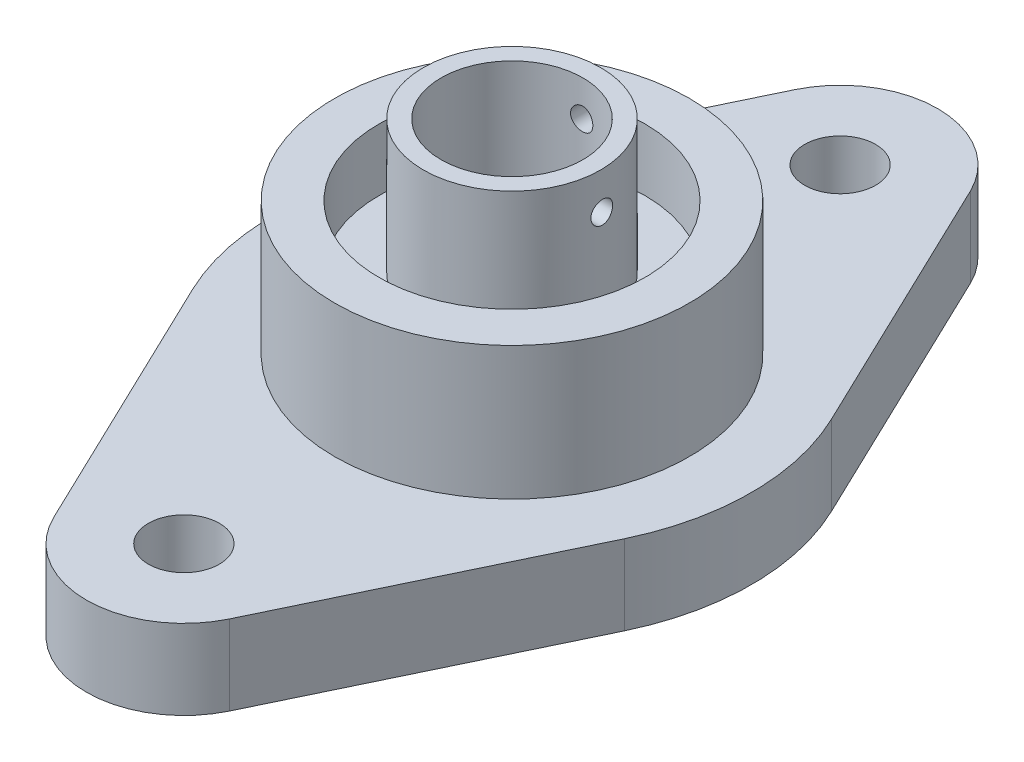
SolidWorks part; units mm, degrees
ref_plane "前视基准面" through (0, 0, 0) normal (0, 0, 1) x (1, 0, 0)
ref_plane "上视基准面" through (0, 0, 0) normal (0, 1, 0) x (1, 0, 0)
ref_plane "右视基准面" through (0, 0, 0) normal (1, 0, 0) x (0, 0, -1)
sketch "草图1" plane through (0, 0, 0) normal (0, 1, 0) x (1, 0, 0)
  circle A0 centre (0, 0) radius 4
  circle A1 centre (0, 0) radius 5
  dimension "D1" = 8
  dimension "D2" = 10
extrude "凸台-拉伸1" add sketch "草图1" along normal blind 16
sketch "草图2" plane through (0, 0, 0) normal (0, -1, 0) x (1, 0, 0)
  circle A0 centre (0, 0) radius 7.5
  circle A1 centre (0, 0) radius 5
  dimension "D1" = 15
  dimension "D2" = 10
extrude "凸台-拉伸2" add sketch "草图2" against normal blind 8.5
sketch "草图3" plane through (0, 0, 0) normal (0, -1, 0) x (1, 0, 0)
  circle A0 centre (0, 0) radius 10
  circle A1 centre (0, 0) radius 7.5
  dimension "D1" = 20
  dimension "D2" = 15
extrude "凸台-拉伸3" add sketch "草图3" against normal blind 12
sketch "草图4" plane through (0, 0, 0) normal (0, -1, 0) x (1, 0, 0)
  line L0 (4.9592, -20.8784) -> (12.1725, -5.8378)
  line L2 (-4.9592, -20.8784) -> (-12.1725, -5.8378)
  line L3 (-12.1725, 5.8378) -> (-4.9592, 20.8784)
  line L4 (12.1725, 5.8378) -> (4.9592, 20.8784)
  circle A0 centre (0, 0) radius 10
  arc A1 (12.1725, -5.8378) -> (12.1725, 5.8378) centre (0, 0) ccw
  circle A2 centre (0, 18.5) radius 2
  circle A3 centre (0, -18.5) radius 2
  circle A4 centre (0, 0) radius 4 construction
  arc A5 (4.9592, 20.8784) -> (-4.9592, 20.8784) centre (0, 18.5) ccw
  arc A6 (-4.9592, -20.8784) -> (4.9592, -20.8784) centre (0, -18.5) ccw
  arc A7 (-12.1725, 5.8378) -> (-12.1725, -5.8378) centre (0, 0) ccw
  dimension "D1" = 20
  dimension "D2" = 27
  dimension "D3" = 4
  dimension "D4" = 4
  dimension "D5" = 18.5
  dimension "D6" = 18.5
  dimension "D9" = 11
  dimension "D10" = 11
  dimension "D7" = 18.5
  dimension "D8" = 18.5
extrude "凸台-拉伸4" add sketch "草图4" against normal blind 4.5
hole_wizard "M1.6 螺纹孔1" positions "3D草图1" profile "草图5" tap size "M1.6" standard "GB"
sketch3d "3D草图1"
  point P0 (4.999, 13.8868, -0.1011)
  point P2 (-0.0284, 13.9831, -4.9999)
sketch "草图5" plane through (4.999, 13.8868, -0.1011) normal (0, 1, 0) x (-0.0202, 0, -0.9998)
  line L0 (0, 0) -> (0, 1)
  line L1 (0, 1) -> (0.625, 1)
  line L2 (0.625, 1) -> (0.625, 0)
  line L5 (0.625, 0) -> (0, 0)
  line L11 (0, -6.35) -> (0, 107.95) construction
  dimension "通孔螺纹孔钻头直径" = 1.25
  dimension "通孔螺纹孔钻头深度" = 1
cosmetic thread "孔螺蚊线1" parameters "D2"=1.6
cosmetic thread "孔螺蚊线2" parameters "D2"=1.6
